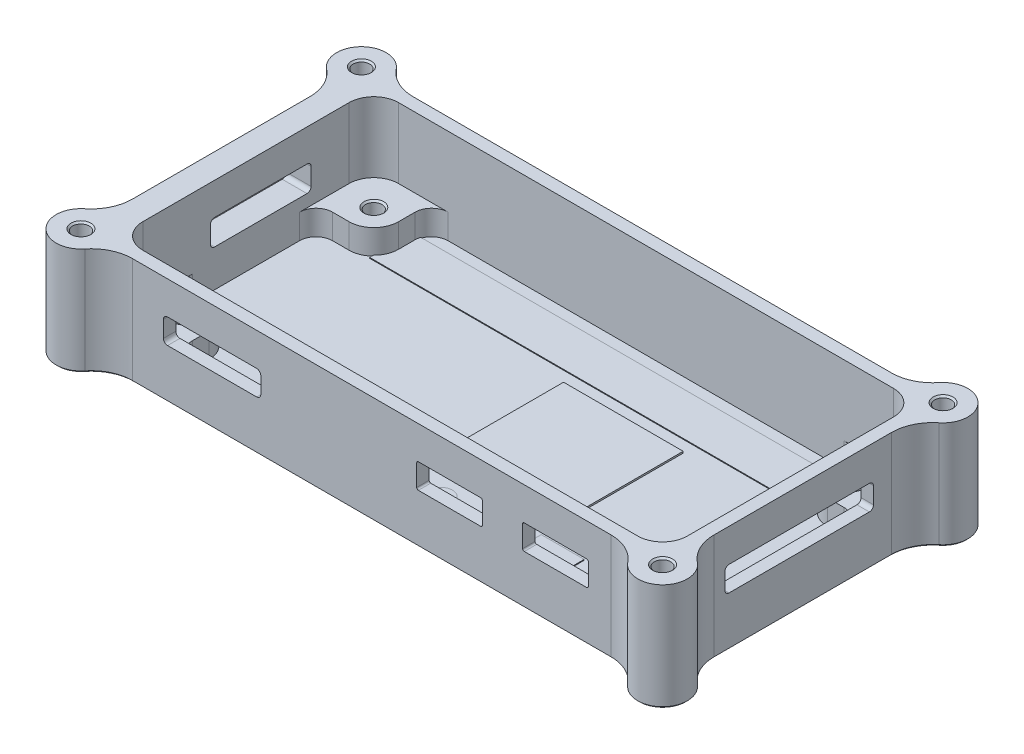
SolidWorks part; units mm, degrees
material "环氧树脂,未充填"
ref_plane "前视基准面" through (0, 0, 0) normal (0, 0, 1) x (1, 0, 0)
ref_plane "上视基准面" through (0, 0, 0) normal (0, 1, 0) x (1, 0, 0)
ref_plane "右视基准面" through (0, 0, 0) normal (1, 0, 0) x (0, 0, -1)
sketch "草图3" plane through (0, 0, 0) normal (0, 1, 0) x (1, 0, 0)
  line L0 (-110.623, 0) -> (88.9187, 0) construction
  line L1 (0, 58.8239) -> (0, -64.236) construction
  line L3 (-33, -15.5) -> (33, -15.5) construction
  line L4 (-33, -15.5) -> (-33, 15.5) construction
  line L5 (-33, 15.5) -> (33, 15.5) construction
  line L6 (33, -15.5) -> (33, 15.5) construction
  line L7 (-33, -15.5) -> (33, 15.5) construction
  line L8 (-33, 15.5) -> (33, -15.5) construction
  line L9 (33, -17.5) -> (-33, -17.5)
  line L10 (36, -14.5) -> (36, 14.5)
  line L11 (33, 17.5) -> (-33, 17.5)
  line L12 (-36, -14.5) -> (-36, 14.5)
  line L13 (36, -17.5) -> (-36, 17.5) construction
  line L14 (36, 17.5) -> (-36, -17.5) construction
  arc A0 (-36, -14.5) -> (-33, -17.5) centre (-33, -14.5) ccw
  arc A1 (33, -17.5) -> (36, -14.5) centre (33, -14.5) ccw
  arc A2 (36, 14.5) -> (33, 17.5) centre (33, 14.5) ccw
  arc A3 (-33, 17.5) -> (-36, 14.5) centre (-33, 14.5) ccw
  point P5 (0, 0)
  point P10 (0, 0)
  dimension "D1" = 3
  dimension "D2" = 72
  dimension "D3" = 35
extrude "凸台-拉伸2" add sketch "草图3" along normal blind 1.5
sketch "草图5" plane through (0, 1.5, 0) normal (0, 1, 0) x (1, 0, 0)
  line L1 (30, -15.5) -> (-30, -15.5)
  line L2 (33, -12.5) -> (33, 12.5)
  line L3 (30, 15.5) -> (-30, 15.5)
  line L4 (-33, -12.5) -> (-33, 12.5)
  line L5 (33, -15.5) -> (-33, 15.5) construction
  line L6 (33, 15.5) -> (-33, -15.5) construction
  line L7 (33, -17.5) -> (-33, -17.5)
  line L8 (36, -14.5) -> (36, 14.5)
  line L9 (33, 17.5) -> (-33, 17.5)
  line L10 (-36, -14.5) -> (-36, 14.5)
  line L11 (36, -17.5) -> (-36, 17.5) construction
  line L12 (36, 17.5) -> (-36, -17.5) construction
  arc A0 (30, 15.5) -> (33, 12.5) centre (30, 12.5) cw
  arc A1 (33, -12.5) -> (30, -15.5) centre (30, -12.5) cw
  arc A2 (-30, -15.5) -> (-33, -12.5) centre (-30, -12.5) cw
  arc A3 (-33, 12.5) -> (-30, 15.5) centre (-30, 12.5) cw
  arc A4 (-36, -14.5) -> (-33, -17.5) centre (-33, -14.5) ccw
  arc A5 (36, -14.5) -> (33, -17.5) centre (33, -14.5) cw
  arc A6 (33, 17.5) -> (36, 14.5) centre (33, 14.5) cw
  arc A7 (-33, 17.5) -> (-36, 14.5) centre (-33, 14.5) ccw
  point P0 (0, 0)
  point P18 (0, 0)
  dimension "D1" = 3
  dimension "D2" = 3
extrude "凸台-拉伸3" add sketch "草图5" along normal blind 11.5
sketch "草图6" plane through (0, 1.5, 0) normal (0, 1, 0) x (1, 0, 0)
  line L0 (-29, 8.5) -> (-33, 8.5)
  line L1 (29, 11.5) -> (-29, 11.5) construction
  line L2 (29, 11.5) -> (29, -11.5) construction
  line L3 (29, -11.5) -> (-29, -11.5) construction
  line L4 (-29, 11.5) -> (-29, -11.5) construction
  line L5 (29, 11.5) -> (-29, -11.5) construction
  line L6 (29, -11.5) -> (-29, 11.5) construction
  line L7 (-26, 11.5) -> (-26, 15.5)
  line L8 (-26, 15.5) -> (-30, 15.5)
  line L11 (-33, 8.5) -> (-33, 12.5)
  line L13 (0, 9.9709) -> (0, -22.1223) construction
  line L14 (-48.3814, 0) -> (44.61, 0) construction
  line L15 (26, 11.5) -> (26, 15.5)
  line L16 (26, 15.5) -> (30, 15.5)
  line L17 (33, 8.5) -> (33, 12.5)
  line L18 (29, 8.5) -> (33, 8.5)
  line L19 (-26, -15.5) -> (-30, -15.5)
  line L20 (-26, -11.5) -> (-26, -15.5)
  line L21 (-29, -8.5) -> (-33, -8.5)
  line L22 (-33, -8.5) -> (-33, -12.5)
  line L23 (29, -8.5) -> (33, -8.5)
  line L24 (33, -8.5) -> (33, -12.5)
  line L25 (26, -15.5) -> (30, -15.5)
  line L26 (26, -11.5) -> (26, -15.5)
  arc A1 (-29, 8.5) -> (-26, 11.5) centre (-29, 11.5) ccw
  arc A2 (-30, 15.5) -> (-33, 12.5) centre (-30, 12.5) ccw
  arc A4 (30, 15.5) -> (33, 12.5) centre (30, 12.5) cw
  arc A5 (29, 8.5) -> (26, 11.5) centre (29, 11.5) cw
  arc A7 (-29, -8.5) -> (-26, -11.5) centre (-29, -11.5) cw
  arc A8 (-30, -15.5) -> (-33, -12.5) centre (-30, -12.5) cw
  arc A10 (29, -8.5) -> (26, -11.5) centre (29, -11.5) ccw
  arc A11 (30, -15.5) -> (33, -12.5) centre (30, -12.5) ccw
  point P0 (0, 0)
  dimension "D1" = 58
  dimension "D2" = 23
extrude "凸台-拉伸6" add sketch "草图6" along normal blind 3
fillet "圆角3" radius 2 8 edges at (33, 3, 8.5) (26, 3, 15.5) (33, 3, -8.5) (26, 3, -15.5) (-26, 3, -15.5) (-33, 3, -8.5) (-33, 3, 8.5) (-26, 3, 15.5)
sketch "草图9" plane through (0, 0, 0) normal (0, -1, 0) x (1, 0, 0)
  line L1 (29, 11.5) -> (-29, 11.5) construction
  line L2 (29, 11.5) -> (29, -11.5) construction
  line L3 (29, -11.5) -> (-29, -11.5) construction
  line L4 (-29, 11.5) -> (-29, -11.5) construction
  line L5 (29, 11.5) -> (-29, -11.5) construction
  line L6 (29, -11.5) -> (-29, 11.5) construction
  point P0 (0, 0)
  dimension "D1" = 58
  dimension "D2" = 23
ref_plane "基准面1" through (0, 0, 11.5) normal (0, 0, 1) x (-1, 0, 0)
sketch "草图11" plane through (0, 0, 11.5) normal (0, 0, 1) x (-1, 0, 0)
  line L1 (29, 0) -> (25.6834, 0)
  line L2 (29, 0) -> (29, 1)
  arc A0 (29, 1) -> (25.6834, 0) centre (29, -5) ccw
revolve "旋转8" add sketch "草图11" angle 360 about L2
ref_plane "基准面3" through (0, 0, 0) normal (0, 0, -1) x (-1, 0, 0)
ref_plane "基准面4" through (0, 0, 0) normal (1, 0, 0) x (0, 0, -1)
mirror "镜向1" about plane through (0, 0, 0) normal (1, 0, 0) of "旋转8"
mirror "镜向2" about plane through (0, 0, 0) normal (0, 0, -1) of "镜向1", "旋转8"
hole_wizard "Ø2.0 (2) 直径孔1" positions "3D草图1" profile "草图12" hole size "Ø2.0" standard "ANSI Metric"
sketch3d "3D草图1"
  line L0 (29, 4.5, -11.5) -> (29, 1.5, -11.5) construction
  line L1 (29, 4.5, 11.5) -> (29, 1.5, 11.5) construction
  line L2 (-29, 4.5, -11.5) -> (-29, 1.5, -11.5) construction
  line L3 (-29, 4.5, 11.5) -> (-29, 1.5, 11.5) construction
  point P0 (29, 4.5, -11.5)
  point P4 (29, 4.5, 11.5)
  point P8 (-29, 4.5, -11.5)
  point P12 (-29, 4.5, 11.5)
sketch "草图12" plane through (29, 4.5, -11.5) normal (1, 0, 0) x (0, 0, 1)
  line L0 (0, 0) -> (0, 4.6009)
  line L1 (0, 4.6009) -> (1, 4)
  line L2 (1, 4) -> (1, 0)
  line L5 (1, 0) -> (0, 0)
  line L10 (0, 4.6009) -> (-1, 4) construction
  line L11 (0, -6.35) -> (0, 107.95) construction
  dimension "孔直径" = 2
  dimension "孔深度" = 4
  dimension "导头角度" = 118
sketch "草图13" plane through (-36, 0, 0) normal (-1, 0, 0) x (0, 0, 1)
  line L0 (0, -3.7657) -> (0, 18.9017) construction
  line L1 (-20.9544, 6) -> (-17.5, 6)
  line L2 (-17.5, 13) -> (-17.5, 0)
  line L6 (-7.9, 6) -> (-7.9, 9.1)
  line L7 (-7.9, 6) -> (4.3, 6)
  line L9 (4.3, 9.1) -> (-7.9, 9.1)
  line L10 (4.3, 9.1) -> (4.3, 6)
  dimension "D1" = 3.1
extrude "切除-拉伸2" cut sketch "草图13" against normal blind 3 contours L9 L6 L7 L10
fillet "圆角4" radius 0.5 4 edges at (-34.5, 6, -7.9) (-34.5, 6, 4.3) (-34.5, 9.1, 4.3) (-34.5, 9.1, -7.9)
sketch "草图14" plane through (0, 0, 17.5) normal (0, 0, 1) x (1, 0, 0)
  line L0 (-33, 13) -> (-33, 0) construction
  line L1 (-33, 0) -> (33, 0) construction
  line L7 (-14.2, 6.5) -> (-14.2, 8.5)
  line L8 (-25.5, 6) -> (-14.7, 6)
  line L9 (-14.7, 9) -> (-25.5, 9)
  line L10 (-26, 8.5) -> (-26, 6.5)
  arc A0 (-26, 6.5) -> (-25.5, 6) centre (-25.5, 6.5) ccw
  arc A1 (-14.7, 6) -> (-14.2, 6.5) centre (-14.7, 6.5) ccw
  arc A2 (-14.2, 8.5) -> (-14.7, 9) centre (-14.7, 8.5) ccw
  arc A3 (-25.5, 9) -> (-26, 8.5) centre (-25.5, 8.5) ccw
  dimension "D1" = 0.5
  dimension "D2" = 3
  dimension "D3" = 7
  dimension "D4" = 6
extrude "切除-拉伸3" cut sketch "草图14" against normal blind 2
sketch "草图15" plane through (36, 0, 0) normal (1, 0, 0) x (0, 0, -1)
  line L5 (8.0644, 6) -> (-8.9356, 6)
  line L6 (-9.4356, 6.5) -> (-9.4356, 8.5)
  line L7 (-8.9356, 9) -> (8.0644, 9)
  line L8 (8.5644, 6.5) -> (8.5644, 8.5)
  arc A0 (8.0644, 9) -> (8.5644, 8.5) centre (8.0644, 8.5) cw
  arc A1 (8.5644, 6.5) -> (8.0644, 6) centre (8.0644, 6.5) cw
  arc A2 (-9.4356, 6.5) -> (-8.9356, 6) centre (-8.9356, 6.5) ccw
  arc A3 (-8.9356, 9) -> (-9.4356, 8.5) centre (-8.9356, 8.5) ccw
  dimension "D1" = 0.5
extrude "切除-拉伸4" cut sketch "草图15" against normal blind 3
sketch "草图16" plane through (0, 0, 17.5) normal (0, 0, 1) x (1, 0, 0)
  line L0 (12.46, 9) -> (4.9, 9)
  line L1 (12.66, 8.8) -> (12.66, 6.2)
  line L2 (17.54, 8.8) -> (17.54, 6.2)
  line L3 (17.74, 6) -> (25.3, 6)
  line L5 (25.5, 6.2) -> (25.5, 8.8)
  line L6 (25.3, 9) -> (17.74, 9)
  line L7 (4.7, 8.8) -> (4.7, 6.2)
  line L8 (4.9, 6) -> (12.46, 6)
  arc A4 (25.5, 8.8) -> (25.3, 9) centre (25.3, 8.8) ccw
  arc A5 (25.3, 6) -> (25.5, 6.2) centre (25.3, 6.2) ccw
  arc A6 (17.74, 6) -> (17.54, 6.2) centre (17.74, 6.2) cw
  arc A7 (17.74, 9) -> (17.54, 8.8) centre (17.74, 8.8) ccw
  arc A8 (4.7, 8.8) -> (4.9, 9) centre (4.9, 8.8) cw
  arc A9 (4.7, 6.2) -> (4.9, 6) centre (4.9, 6.2) ccw
  arc A10 (12.46, 6) -> (12.66, 6.2) centre (12.46, 6.2) ccw
  arc A11 (12.66, 8.8) -> (12.46, 9) centre (12.46, 8.8) ccw
  point P0 (15, 9)
  point P1 (15, 3.8111)
  point P2 (12.66, 9)
  point P3 (12.46, 3.8111)
  point P4 (17.54, 9)
  point P17 (17.54, 3.8111)
  dimension "D2" = 0.2
extrude "切除-拉伸5" cut sketch "草图16" against normal blind 2
chamfer "倒角1" distance 0.2 angle 45 4 edges at (-29, 4.5, 12.5) (29, 4.5, 12.5) (29, 4.5, -10.5) (-29, 4.5, -10.5)
sketch "草图17" plane through (0, 0, 0) normal (0, -1, 0) x (1, 0, 0)
  line L0 (-36, 14) -> (-36, -14)
  line L6 (-33, -17) -> (31.5, -17)
  line L9 (34.5, 14) -> (34.5, -14)
  line L11 (-33, 17) -> (31.5, 17)
  line L12 (40, -20) -> (-40, -20)
  line L13 (40, -20) -> (40, 20)
  line L14 (40, 20) -> (-40, 20)
  line L15 (-40, -20) -> (-40, 20)
  line L16 (40, -20) -> (-40, 20) construction
  line L17 (40, 20) -> (-40, -20) construction
  arc A0 (34.5, -14) -> (31.5, -17) centre (31.5, -14) cw
  arc A1 (-36, -14) -> (-33, -17) centre (-33, -14) ccw
  arc A2 (34.5, 14) -> (31.5, 17) centre (31.5, 14) ccw
  arc A3 (-33, 17) -> (-36, 14) centre (-33, 14) ccw
  point P2 (0, 0)
  dimension "D1" = 3
  dimension "D2" = 3
  dimension "D3" = 3
extrude "切除-拉伸6" cut sketch "草图17" against normal blind 15
sketch "草图20" plane through (0, 13, 0) normal (0, 1, 0) x (1, 0, 0)
  circle A0 centre (-36, 17) radius 3
  circle A1 centre (-36, -17) radius 3
  circle A2 centre (34.5, -17) radius 3
  circle A3 centre (34.5, 17) radius 3
  circle A4 centre (-36, 17) radius 1
  circle A5 centre (34.5, 17) radius 1
  circle A6 centre (34.5, -17) radius 1
  circle A7 centre (-36, -17) radius 1
extrude "凸台-拉伸11" add sketch "草图20" against normal blind 13
fillet "圆角7" radius 5 8 edges at (-36, 6.5, 14) (-33, 6.5, 17) (31.5, 6.5, 17) (34.5, 6.5, 14) (-33, 6.5, -17) (-36, 6.5, -14) (31.5, 6.5, -17) (34.5, 6.5, -14)
sketch "草图21" plane through (0, 1.5, 0) normal (0, 1, 0) x (1, 0, 0)
  line L3 (12.55, -7.05) -> (-1.95, -7.05)
  line L4 (12.55, -7.05) -> (12.55, 7.45)
  line L5 (12.55, 7.45) -> (-1.95, 7.45)
  line L6 (-1.95, -7.05) -> (-1.95, 7.45)
  line L7 (12.55, -7.05) -> (-1.95, 7.45) construction
  line L8 (12.55, 7.45) -> (-1.95, -7.05) construction
  dimension "D1" = 14.5
  dimension "D2" = 14.5
extrude "凸台-拉伸12" add sketch "草图21" along normal blind 0.2
sketch "草图22" plane through (0, 1.5, 0) normal (0, 1, 0) x (1, 0, 0)
  line L0 (-26.9, 14.1) -> (26.9, 14.1)
  line L1 (-26.9, 11.5) -> (-26.9, 8.9)
  line L3 (26.9, 14.1) -> (26.9, 8.9)
  line L4 (26.9, 8.9) -> (-26.9, 8.9)
  line L5 (-26.9, 11.5) -> (-26.9, 14.1)
extrude "凸台-拉伸13" add sketch "草图22" along normal blind 0.1
sketch "草图23" plane through (0, 1.5, 0) normal (0, 1, 0) x (1, 0, 0)
  line L1 (17.8, -15) -> (17.8, -9.8)
  line L2 (17.8, -15) -> (12.6, -15)
  line L3 (12.6, -9.8) -> (12.6, -15)
  line L4 (12.6, -9.8) -> (17.8, -9.8)
extrude "凸台-拉伸14" add sketch "草图23" along normal blind 0.1
sketch "草图24" plane through (0, 1.5, 0) normal (0, 1, 0) x (1, 0, 0)
  circle A0 centre (2.54, -11.913) radius 1.4
  circle A1 centre (-1.016, -11.913) radius 1.4
extrude "凸台-拉伸15" add sketch "草图24" along normal blind 0.1
chamfer "倒角2" distance 0.2 angle 45 16 edges at (30.4201, 0, 17.4931) (36.6213, 0, 19.1213) (34.9931, 0, 12.9201) (34.5, 0, 0) (34.9931, 0, -12.9201) (36.6213, 0, -19.1213) (30.4201, 0, -17.4931) (-0.75, 0, 17) (-31.9201, 0, 17.4931) (-38.1213, 0, 19.1213) (-36.4931, 0, 12.9201) (-36, 0, 0) (-36.4931, 0, -12.9201) (-38.1213, 0, -19.1213) (-31.9201, 0, -17.4931) (-0.75, 0, -17)
chamfer "倒角3" distance 0.2 angle 45 8 edges at (-36, 0, 18) (-36, 13, 18) (-36, 0, -16) (-36, 13, -16) (34.5, 0, -16) (34.5, 13, -16) (34.5, 0, 18) (34.5, 13, 18)
sketch "草图25" plane through (0, 1.5, 0) normal (0, 1, 0) x (1, 0, 0)
  line L1 (-24.5, -7.6) -> (-32.5, -7.6)
  line L2 (-32.5, -7.6) -> (-32.5, -5)
  line L3 (-32.5, -5) -> (-24.5, -5)
  line L4 (-24.5, -5) -> (-24.5, -7.6)
extrude "凸台-拉伸16" add sketch "草图25" along normal blind 0.1
